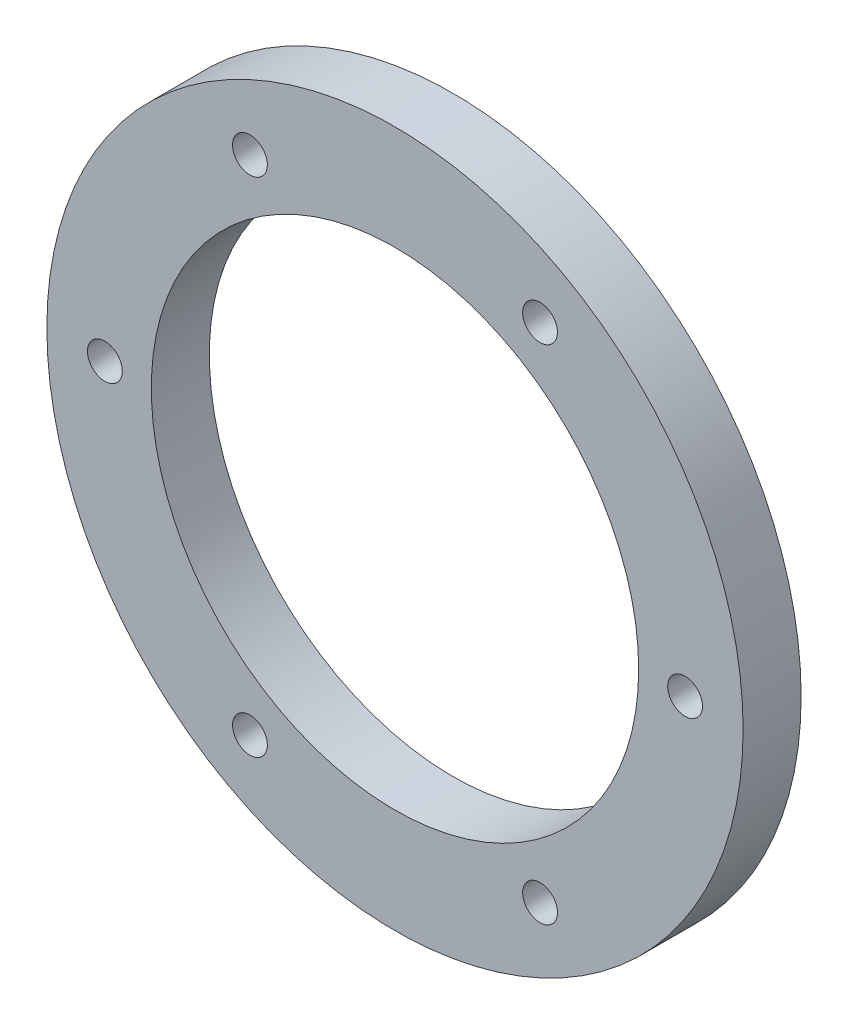
SolidWorks part; units mm, degrees
material "Acrylic (Medium-high impact)"
ref_plane "Front Plane" through (0, 0, 0) normal (0, 0, 1) x (1, 0, 0)
ref_plane "Top Plane" through (0, 0, 0) normal (0, 1, 0) x (1, 0, 0)
ref_plane "Right Plane" through (0, 0, 0) normal (1, 0, 0) x (0, 0, -1)
sketch "Sketch1" plane through (0, 0, 0) normal (0, 0, 1) x (1, 0, 0)
  line L0 (0, 34.8882) -> (0, -35.3531) construction
  line L1 (0, -35.3531) -> (0, 0) construction
  line L2 (0, 0) -> (-48.3544, 0) construction
  line L3 (-48.3544, 0) -> (47.9766, 0) construction
  line L4 (-26.5908, 46.0566) -> (27.6893, -47.9592) construction
  line L5 (27.6893, -47.9592) -> (0, 0) construction
  line L6 (0, 0) -> (21.8015, 37.7613) construction
  line L7 (0, 0) -> (-24.3439, -42.1648) construction
  circle A0 centre (0, 0) radius 30
  circle A2 centre (0, 0) radius 21
  circle A7 centre (0, 0) radius 25 construction
  circle A8 centre (-12.5, 21.6506) radius 1.5
  circle A9 centre (-25, 0) radius 1.5
  circle A10 centre (-12.5, -21.6506) radius 1.5
  circle A12 centre (12.5, -21.6506) radius 1.5
  circle A13 centre (25, 0) radius 1.5
  circle A14 centre (12.5, 21.6506) radius 1.5
  dimension "D2" = 60
  dimension "D4" = 3
  dimension "D5" = 3
  dimension "D3" = 60
extrude "Boss-Extrude1" add sketch "Sketch1" along normal blind 5
